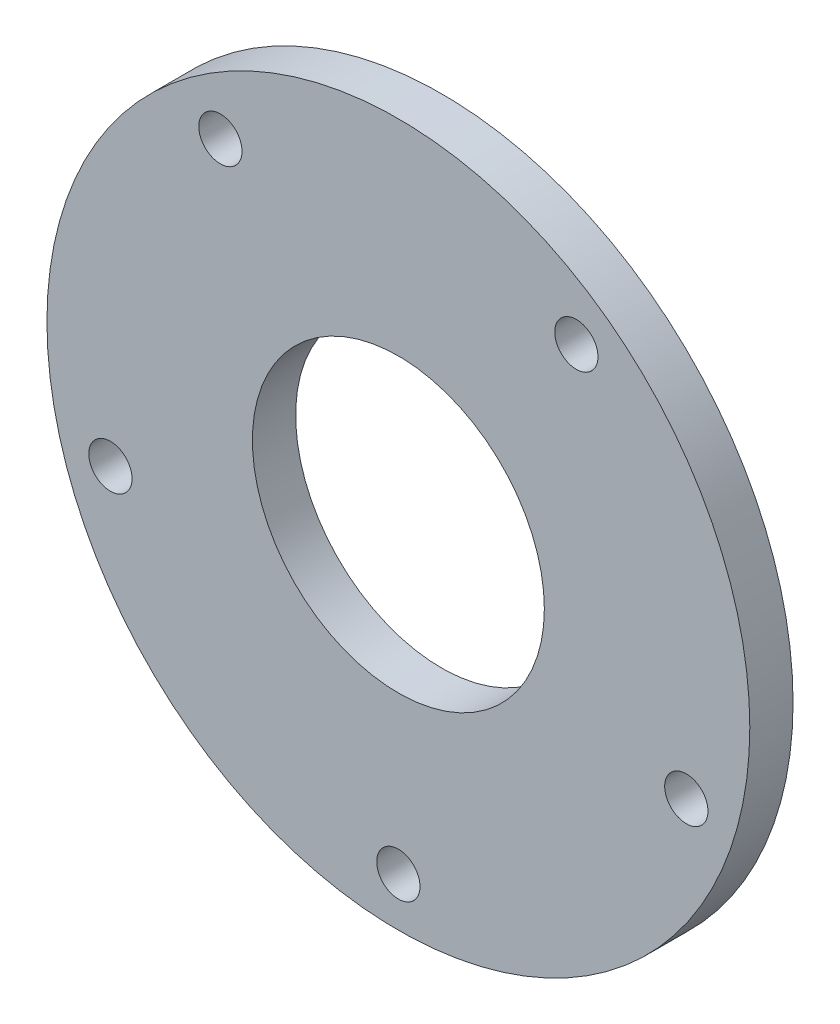
SolidWorks part; units mm, degrees
ref_plane "前视基准面" through (0, 0, 0) normal (0, 0, 1) x (1, 0, 0)
ref_plane "上视基准面" through (0, 0, 0) normal (0, 1, 0) x (1, 0, 0)
ref_plane "右视基准面" through (0, 0, 0) normal (1, 0, 0) x (0, 0, -1)
sketch "草图1" plane through (0, 0, 0) normal (0, 0, 1) x (1, 0, 0)
  line L0 (-26.6296, -8.6525) -> (0, -28) construction
  line L1 (-13.3148, -18.3262) -> (-4.9931, -6.8724) construction
  circle A0 centre (0, 0) radius 32.5
  circle A1 centre (0, 0) radius 13.5
  circle A2 centre (0, -28) radius 2
  circle A3 centre (-26.6296, -8.6525) radius 2
  circle A4 centre (-16.458, 22.6525) radius 2
  circle A5 centre (16.458, 22.6525) radius 2
  circle A6 centre (26.6296, -8.6525) radius 2
  dimension "D1" = 65
  dimension "D3" = 27
extrude "凸台-拉伸1" add sketch "草图1" along normal blind 4 contours A1
